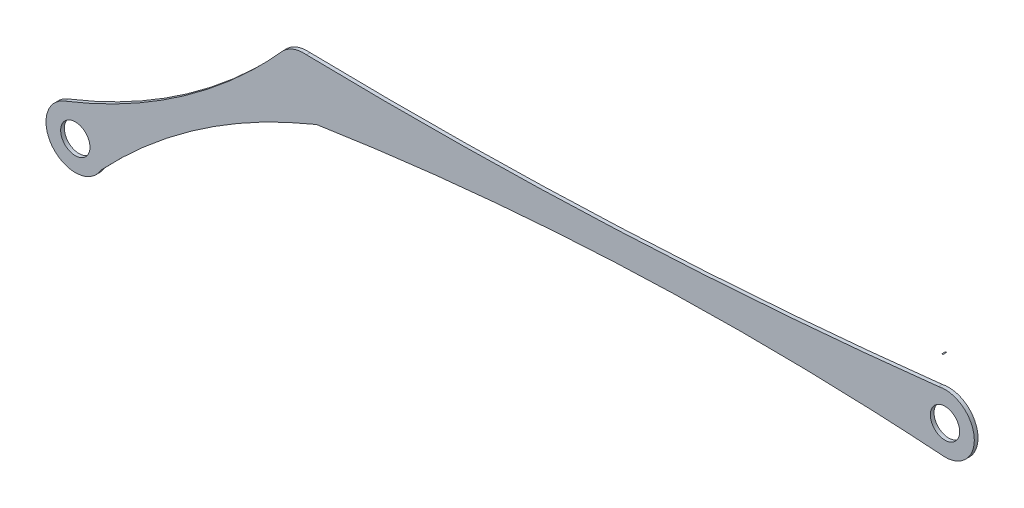
SolidWorks part; units mm, degrees
material "1060 Alloy"
ref_plane "Front Plane" through (0, 0, 0) normal (0, 0, 1) x (1, 0, 0)
ref_plane "Top Plane" through (0, 0, 0) normal (0, 1, 0) x (1, 0, 0)
ref_plane "Right Plane" through (0, 0, 0) normal (1, 0, 0) x (0, 0, -1)
sketch "Sketch1" plane through (0, 0, 0) normal (0, 0, 1) x (1, 0, 0)
  line L0 (0, 0) -> (279.4, 0) construction
  line L1 (7.0023, 16.6052) -> (278.5791, 25.3867)
  line L2 (16.974, -33.8989) -> (280.2209, -25.3867)
  line L3 (0, 0) -> (-97.2876, -81.634) construction
  line L4 (2.6264, -38.9122) -> (-82.1191, -102.0074)
  line L5 (-10.5891, 14.582) -> (-112.4562, -61.2606)
  arc A0 (7.0023, 16.6052) -> (-10.5891, 14.582) centre (0, 0) ccw
  arc A1 (280.2209, -25.3867) -> (278.5791, 25.3867) centre (279.4, 0) ccw
  arc A3 (-112.4562, -61.2606) -> (-82.1191, -102.0074) centre (-97.2876, -81.634) ccw
  arc A4 (0, 18.0212) -> (-10.5891, 14.582) centre (0, 0) ccw
  arc A5 (2.6264, -38.9122) -> (16.974, -33.8989) centre (17.7949, -59.2856) cw
  circle A6 centre (-97.2876, -81.634) radius 6.35
  circle A7 centre (279.4, 0) radius 6.35
  point P3 (114.3, 0)
  point P10 (-50.9335, -37.9213)
  dimension "D2" = 127
  dimension "D3" = 50.8
  dimension "D4" = 12.7
  dimension "D5" = 12.7
  dimension "D8" = 25.4
  dimension "D9" = 25.4
  dimension "D1" = 279.4
  dimension "D6" = 140
  dimension "D7" = 50.8
extrude "Boss-Extrude1" add sketch "Sketch1" along normal blind 1.6002 contours L4 A5 L2 A1 L1 A0 L5 A3 A7 A6
sketch "Sketch2" plane through (0, 0, 1.6002) normal (0, 0, 1) x (1, 0, 0)
  line L0 (16.974, -33.8989) -> (280.2209, -25.3867) construction
  line L1 (7.0023, 16.6052) -> (278.5791, 25.3867) construction
  line L2 (-97.2876, -81.634) -> (1.5952, -12.7) construction
  line L3 (-134.3295, -73.2391) -> (-53.9694, -4.7447)
  line L4 (-93.0845, -119.382) -> (5.3912, -67.5917)
  line L5 (279.4, 0) -> (1.5952, -12.7) construction
  line L6 (280.56, -25.3735) -> (5.3912, -67.5917)
  line L7 (278.24, 25.3735) -> (46.7414, 20.6549)
  arc A0 (-101.7594, -69.7473) -> (-86.2073, -87.8401) centre (-97.2876, -81.634) ccw
  arc A1 (277.6706, -12.5817) -> (276.5811, 12.3832) centre (279.4, 0) ccw
  arc A2 (5.3912, -24.8194) -> (7.3439, -24.0245) centre (1.5952, -12.7) ccw
  arc A3 (16.974, -33.8989) -> (2.6264, -38.9122) centre (17.7949, -59.2856) ccw construction
  arc A4 (2.8221, -0.0594) -> (-8.3044, -4.7447) centre (1.5952, -12.7) ccw
  arc A5 (-134.3295, -73.2391) -> (-93.0845, -119.382) centre (-97.2876, -81.634) ccw
  arc A6 (46.7414, 20.6549) -> (-53.9694, -4.7447) centre (1.5952, -12.7) ccw
  arc A7 (280.56, -25.3735) -> (278.24, 25.3735) centre (279.4, 0) ccw
  arc A8 (46.7414, 20.6549) -> (-30.5051, 33.3466) centre (1.5952, -12.7) ccw
  spline S0 degree 2 poles (7.3439, -24.0245) (-46.6543, -45.771) (-86.2073, -87.8401) knots 0 0 0 1 1 1
  spline S1 degree 2 poles (-102.152, -69.9025) (-47.7798, -48.4603) (-8.3044, -4.7447) knots 0 0 0 1 1 1
  spline S2 degree 2 poles (0, 0) (140.154, -3.0443) (279.4, 12.7) knots 0 0 0 1 1 1
  spline S3 degree 2 poles (7.3439, -24.0245) (142.7973, -3.2601) (279.4, -12.7) knots 0 0 0 1 1 1
  point P4 (-47.8462, -47.167)
  point P20 (9.4165, -35.3073)
  point P35 (140.4976, -6.35)
  dimension "D1" = 25.4
  dimension "D2" = 25.4
  dimension "D3" = 22.6073
  dimension "D4" = 19.05
  dimension "D5" = 19.05
extrude "Cut-Extrude1" cut sketch "Sketch2" against normal through all
